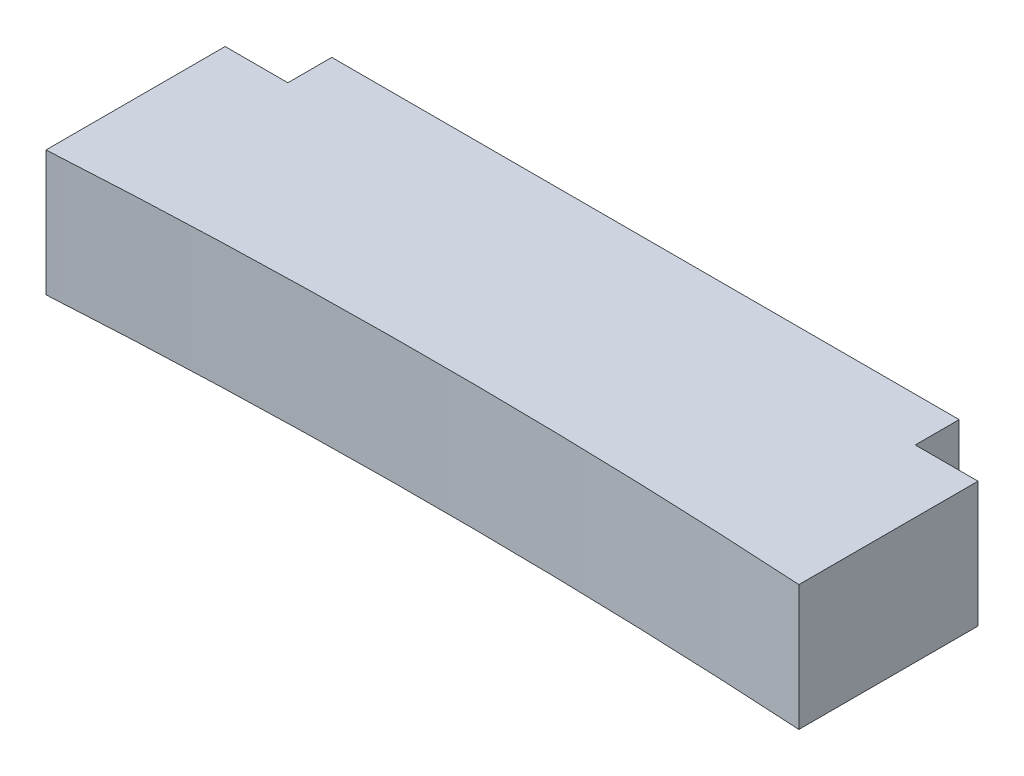
SolidWorks part; units mm, degrees
material "6061-T6 (SS)"
ref_plane "Front Plane" through (0, 0, 0) normal (0, 0, 1) x (1, 0, 0)
ref_plane "Top Plane" through (0, 0, 0) normal (0, 1, 0) x (1, 0, 0)
ref_plane "Right Plane" through (0, 0, 0) normal (1, 0, 0) x (0, 0, -1)
sketch "Sketch1" plane through (0, 0, 0) normal (0, 1, 0) x (1, 0, 0)
  line L0 (-20, 0) -> (0, 0)
  line L1 (24, -2.8) -> (24, -14.2206)
  line L2 (-24, -2.8) -> (-24, -14.2206)
  line L3 (-24, -13.5) -> (24, -13.5) construction
  line L4 (-20, 0) -> (-20, -2.8)
  line L5 (-20, -2.8) -> (-24, -2.8)
  line L6 (20, 0) -> (20, -2.8)
  line L7 (20, -2.8) -> (24, -2.8)
  line L22 (0, 0) -> (20, 0)
  line L25 (-24, -14.2206) -> (0, -413.5) construction
  line L26 (0, -413.5) -> (24, -14.2206) construction
  arc A0 (-24, -14.2206) -> (24, -14.2206) centre (0, -413.5) cw
  dimension "D1" = 13.5
  dimension "D2" = 400
  dimension "D3" = 2.8
  dimension "D4" = 20
  dimension "D5" = 48
extrude "Boss-Extrude1" add sketch "Sketch1" along normal mid plane 8
sketch "Sketch5" plane through (0, 4, 0) normal (0, 1, 0) x (1, 0, 0)
  line L4 (-20, 0) -> (-20, 16) construction
  line L5 (0, 0) -> (0, 18.0283) construction
  line L8 (20, 0) -> (20, 16) construction
  line L17 (-20, 16) -> (-15.6, 16)
  line L19 (-15.6, 16) -> (-15.6, 0)
  line L20 (20, 0) -> (-20, 0) construction
  line L22 (-15.6, 0) -> (-20, 0)
  line L24 (-20, 16) -> (-24, -2.8)
  line L25 (-24, -2.8) -> (-20, -2.8)
  line L26 (-20, -2.8) -> (-20, 0)
  line L27 (20, -2.8) -> (20, 0)
  line L28 (24, -2.8) -> (20, -2.8)
  line L29 (20, 16) -> (24, -2.8)
  line L30 (15.6, 0) -> (20, 0)
  line L31 (15.6, 16) -> (15.6, 0)
  line L32 (20, 16) -> (15.6, 16)
  dimension "D1" = 4.4
  dimension "D2" = 16
extrude "Boss-Extrude2" [suppressed] add sketch "Sketch5" against normal up to surface (8 mm away)
